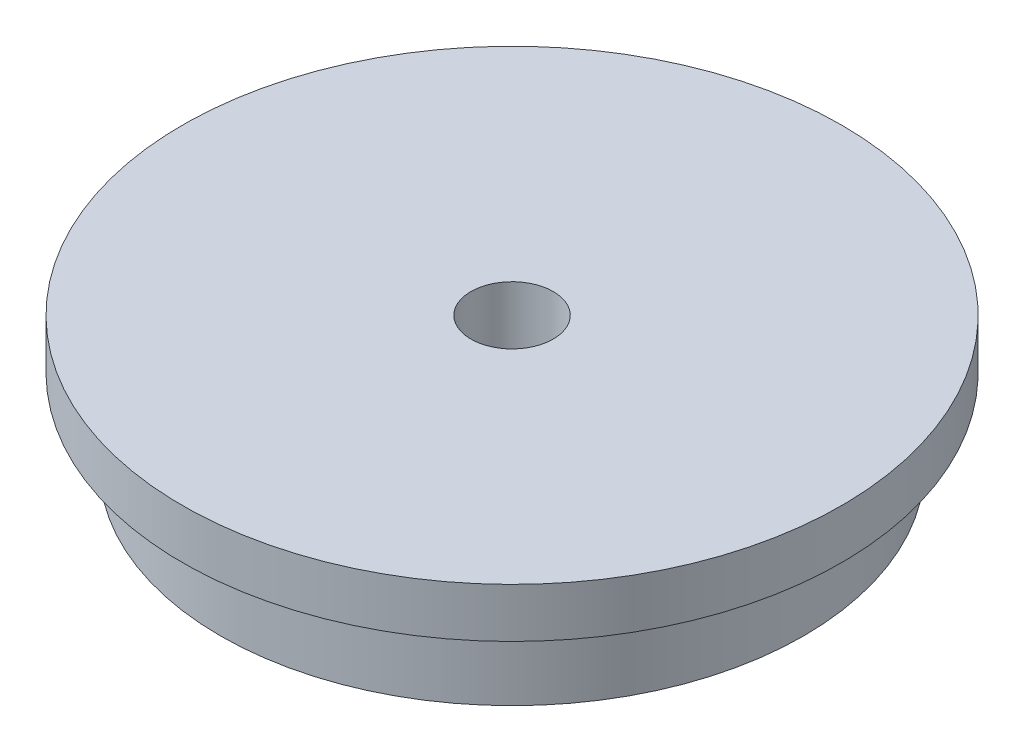
SolidWorks part; units mm, degrees
ref_plane "Front Plane" through (0, 0, 0) normal (0, 0, 1) x (1, 0, 0)
ref_plane "Top Plane" through (0, 0, 0) normal (0, 1, 0) x (1, 0, 0)
ref_plane "Right Plane" through (0, 0, 0) normal (1, 0, 0) x (0, 0, -1)
sketch "Sketch1" plane through (0, 0, 0) normal (0, 1, 0) x (1, 0, 0)
  circle A0 centre (0, 0) radius 22.479
  dimension "D1" = 44.958
extrude "Boss-Extrude1" add sketch "Sketch1" along normal blind 6.35
sketch "Sketch2" plane through (0, 6.35, 0) normal (0, 1, 0) x (1, 0, 0)
  circle A0 centre (0, 0) radius 25.4
  dimension "D1" = 50.8
extrude "Boss-Extrude2" add sketch "Sketch2" along normal blind 3.81
sketch "Sketch3" plane through (0, 0, 0) normal (0, -1, 0) x (1, 0, 0)
  circle A0 centre (0, 0) radius 8.9916
  dimension "D1" = 17.9832
extrude "Cut-Extrude1" cut sketch "Sketch3" against normal blind 3.81
sketch "Sketch4" plane through (0, 3.81, 0) normal (0, -1, 0) x (1, 0, 0)
  circle A0 centre (0, 0) radius 3.175
  dimension "D1" = 6.35
extrude "Cut-Extrude2" cut sketch "Sketch4" against normal through all
